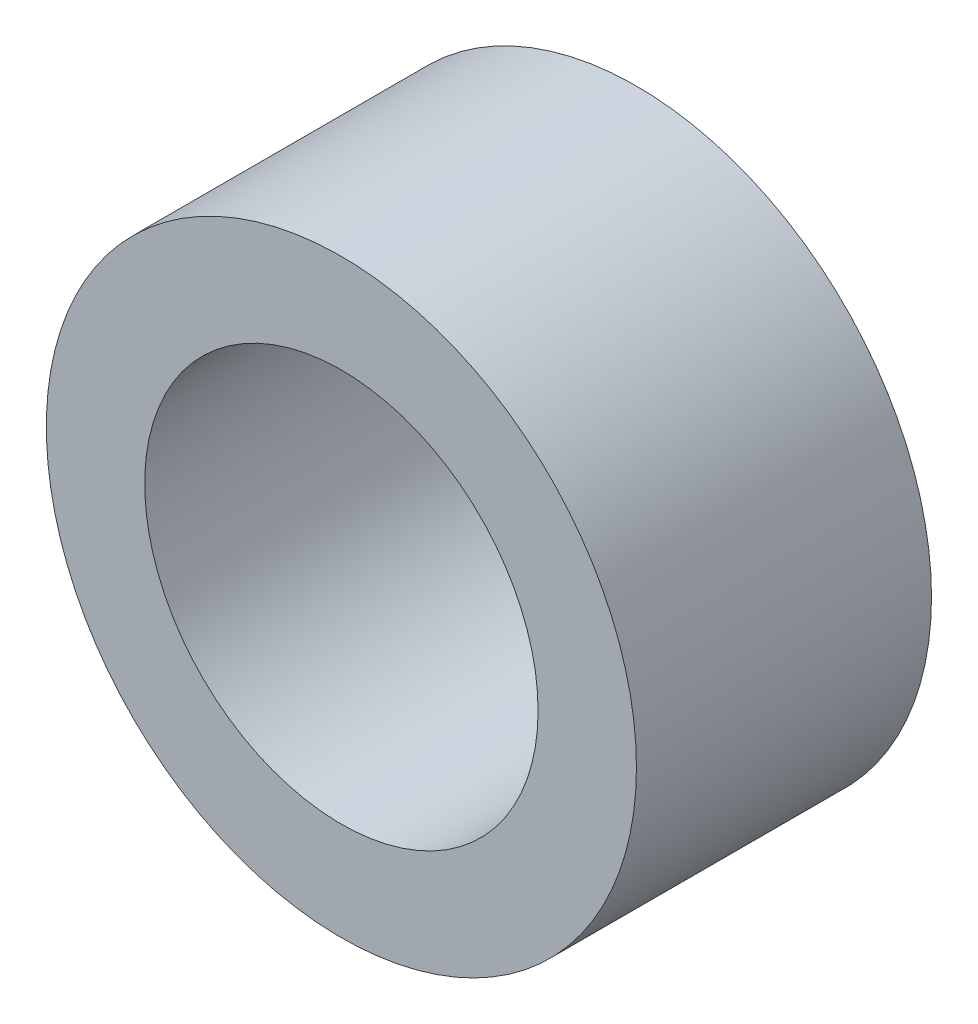
SolidWorks part; units mm, degrees
material "合金钢"
ref_plane "前视基准面" through (0, 0, 0) normal (0, 0, 1) x (1, 0, 0)
ref_plane "上视基准面" through (0, 0, 0) normal (0, 1, 0) x (1, 0, 0)
ref_plane "右视基准面" through (0, 0, 0) normal (1, 0, 0) x (0, 0, -1)
other "Configuration Table"
sketch "草图1" plane through (0, 0, 0) normal (0, 0, 1) x (1, 0, 0)
  line L0 (-13.6576, 0) -> (3.201, 0) construction
  line L1 (0, 5.8551) -> (0, -4.7348) construction
  circle A0 centre (0, 0) radius 2
  circle A1 centre (0, 0) radius 3
  dimension "D1" = 4
  dimension "D2" = 6
extrude "凸台-拉伸1" add sketch "草图1" along normal blind 3
